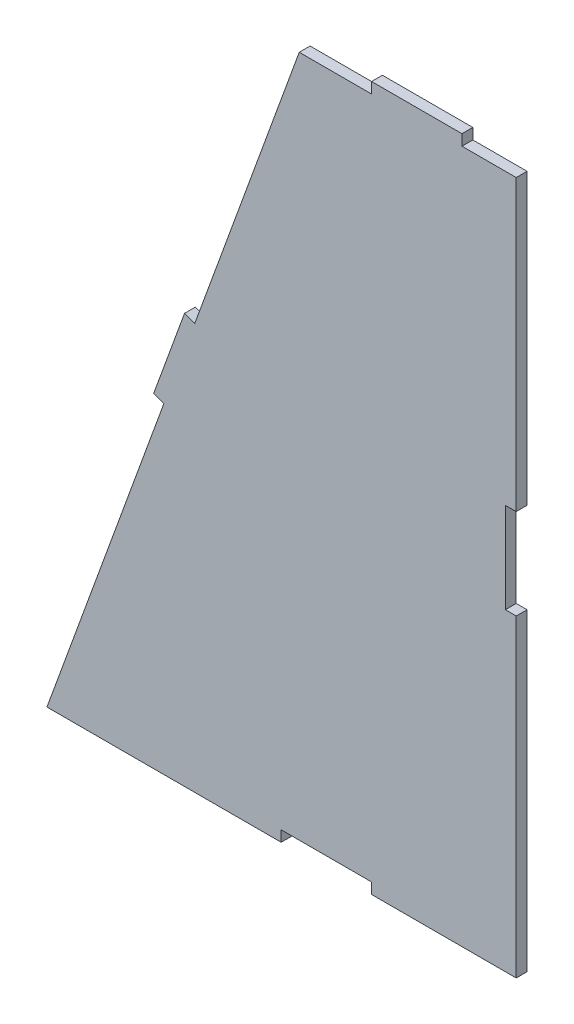
SolidWorks part; units mm, degrees
ref_plane "Спереди" through (0, 0, 0) normal (0, 0, 1) x (1, 0, 0)
ref_plane "Сверху" through (0, 0, 0) normal (0, 1, 0) x (1, 0, 0)
ref_plane "Справа" through (0, 0, 0) normal (1, 0, 0) x (0, 0, -1)
sketch "Эскиз1" plane through (0, 0, 0) normal (0, 0, 1) x (1, 0, 0)
  line L0 (-38.4665, 0) -> (26.3056, 0)
  line L1 (91.3056, 0) -> (91.3056, 86.6973)
  line L2 (91.3056, 191.6973) -> (76.3056, 191.6973)
  line L3 (31.3056, 191.6973) -> (2.4049, 112.2933)
  line L4 (2.4049, 112.2933) -> (-0.4142, 113.3193)
  line L5 (-0.4142, 113.3193) -> (-8.9647, 89.827)
  line L6 (-8.9647, 89.827) -> (-6.1456, 88.801)
  line L7 (-6.1456, 88.801) -> (-38.4665, 0)
  line L8 (91.3056, 111.6973) -> (88.3056, 111.6973)
  line L9 (88.3056, 111.6973) -> (88.3056, 86.6973)
  line L10 (88.3056, 86.6973) -> (91.3056, 86.6973)
  line L11 (51.3056, 0) -> (91.3056, 0)
  line L13 (26.3056, 0) -> (26.3056, 3)
  line L14 (26.3056, 3) -> (51.3056, 3)
  line L15 (51.3056, 0) -> (51.3056, 3)
  line L16 (91.3056, 111.6973) -> (91.3056, 191.6973)
  line L17 (51.3056, 191.6973) -> (31.3056, 191.6973)
  line L19 (51.3056, 191.6973) -> (51.3056, 194.6973)
  line L20 (51.3056, 194.6973) -> (76.3056, 194.6973)
  line L21 (76.3056, 191.6973) -> (76.3056, 194.6973)
  dimension "D1" = 70
  dimension "D2" = 70
  dimension "D3" = 25
  dimension "D4" = 204
  dimension "D5" = 84.5
  dimension "D6" = 3
  dimension "D7" = 60
  dimension "D8" = 129.7721
  dimension "D9" = 191.6973
  dimension "D10" = 25
  dimension "D11" = 3
  dimension "D12" = 80
  dimension "D13" = 25
  dimension "D14" = 3
  dimension "D15" = 40
  dimension "D16" = 25
  dimension "D17" = 3
  dimension "D18" = 15
extrude "Бобышка-Вытянуть1" add sketch "Эскиз1" along normal blind 3
